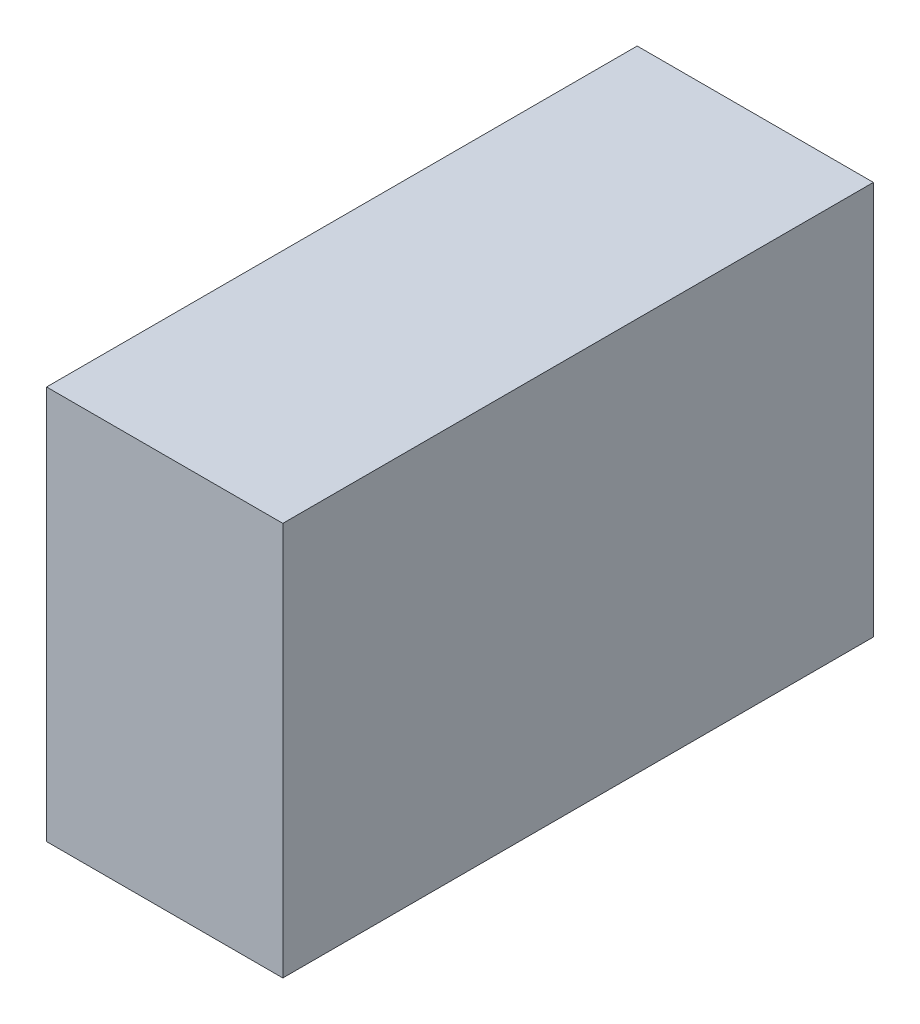
SolidWorks part; units mm, degrees
ref_plane "Front Plane" through (0, 0, 0) normal (0, 0, 1) x (1, 0, 0)
ref_plane "Top Plane" through (0, 0, 0) normal (0, 1, 0) x (1, 0, 0)
ref_plane "Right Plane" through (0, 0, 0) normal (1, 0, 0) x (0, 0, -1)
sketch "Sketch1" plane through (0, 0, 0) normal (0, 1, 0) x (1, 0, 0)
  line L1 (-6, -15) -> (6, -15)
  line L2 (-6, -15) -> (-6, 15)
  line L3 (-6, 15) -> (6, 15)
  line L4 (6, -15) -> (6, 15)
  line L5 (-6, -15) -> (6, 15) construction
  line L6 (-6, 15) -> (6, -15) construction
  point P0 (0, 0)
  dimension "D1" = 30
  dimension "D2" = 12
extrude "Boss-Extrude1" add sketch "Sketch1" along normal blind 20
